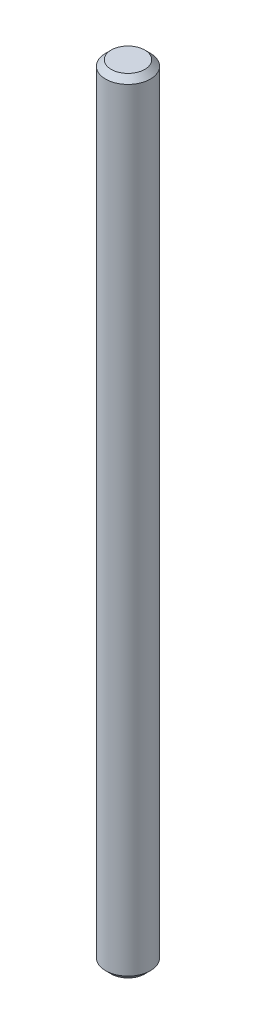
SolidWorks part; units mm, degrees
ref_plane "Front Plane" through (0, 0, 0) normal (0, 0, 1) x (1, 0, 0)
ref_plane "Top Plane" through (0, 0, 0) normal (0, 1, 0) x (1, 0, 0)
ref_plane "Right Plane" through (0, 0, 0) normal (1, 0, 0) x (0, 0, -1)
sketch "Sketch2" plane through (0, 0, 0) normal (0, 1, 0) x (1, 0, 0)
  circle A0 centre (0, 0) radius 4
  dimension "D1" = 8
extrude "Boss-Extrude2" add sketch "Sketch2" along normal blind 140
chamfer "Chamfer1" distance 1 angle 45 2 edges at (0, 0, 4) (0, 140, 4)
